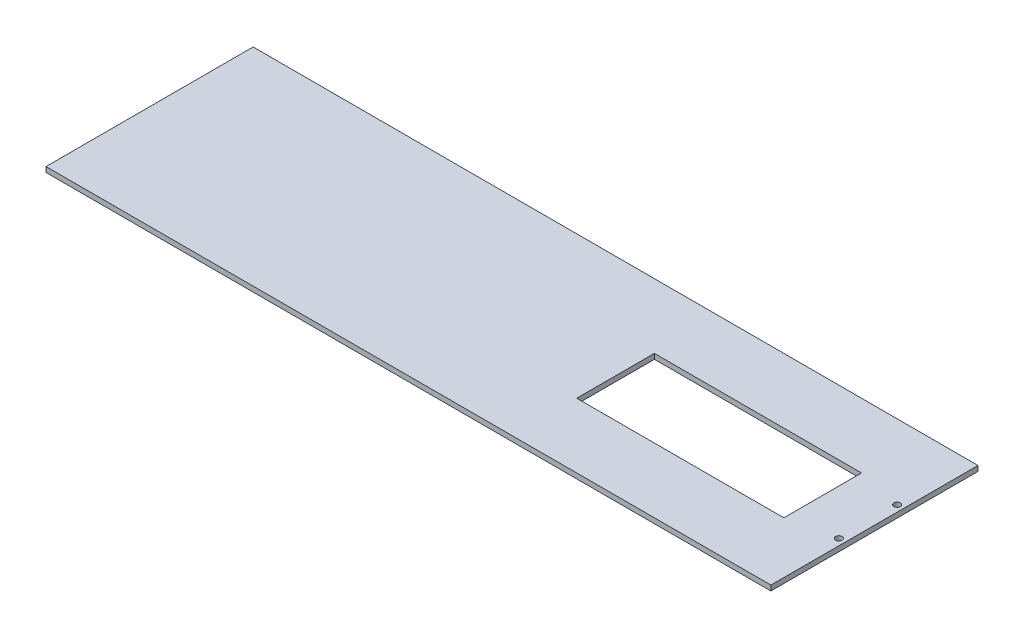
SolidWorks part; units mm, degrees
ref_plane "Front Plane" through (0, 0, 0) normal (0, 0, 1) x (1, 0, 0)
ref_plane "Top Plane" through (0, 0, 0) normal (0, 1, 0) x (1, 0, 0)
ref_plane "Right Plane" through (0, 0, 0) normal (1, 0, 0) x (0, 0, -1)
sketch "Sketch1" plane through (0, 0, 0) normal (0, 1, 0) x (1, 0, 0)
  line L1 (-177.8, -50.8) -> (177.8, -50.8)
  line L2 (-177.8, -50.8) -> (-177.8, 50.8)
  line L3 (-177.8, 50.8) -> (177.8, 50.8)
  line L4 (177.8, -50.8) -> (177.8, 50.8)
  line L5 (-177.8, -50.8) -> (177.8, 50.8) construction
  line L6 (-177.8, 50.8) -> (177.8, -50.8) construction
  point P0 (0, 0)
  dimension "D1" = 101.6
  dimension "D2" = 355.6
extrude "Boss-Extrude1" add sketch "Sketch1" along normal blind 2.54
sketch "Sketch3" plane through (0, 2.54, 0) normal (0, 1, 0) x (1, 0, 0)
  line L0 (177.8, -50.8) -> (177.8, 50.8) construction
  line L1 (152.4, -19.05) -> (50.8, -19.05)
  line L2 (152.4, -19.05) -> (152.4, 19.05)
  line L3 (152.4, 19.05) -> (50.8, 19.05)
  line L4 (50.8, -19.05) -> (50.8, 19.05)
  line L5 (152.4, -19.05) -> (50.8, 19.05) construction
  line L6 (152.4, 19.05) -> (50.8, -19.05) construction
  line L7 (174.625, -14.2875) -> (174.625, 14.2875) construction
  line L8 (-177.8, 50.8) -> (-177.8, -50.8) construction
  circle A0 centre (174.625, -14.2875) radius 1.5875
  circle A1 centre (174.625, 14.2875) radius 1.5875
  point P0 (101.6, 0)
  point P12 (174.625, 0)
  dimension "D5" = 3.175
  dimension "D1" = 25.4
  dimension "D2" = 101.6
  dimension "D3" = 38.1
  dimension "D4" = 28.575
  dimension "D6" = 3.175
extrude "Cut-Extrude1" cut sketch "Sketch3" against normal blind 2.54
